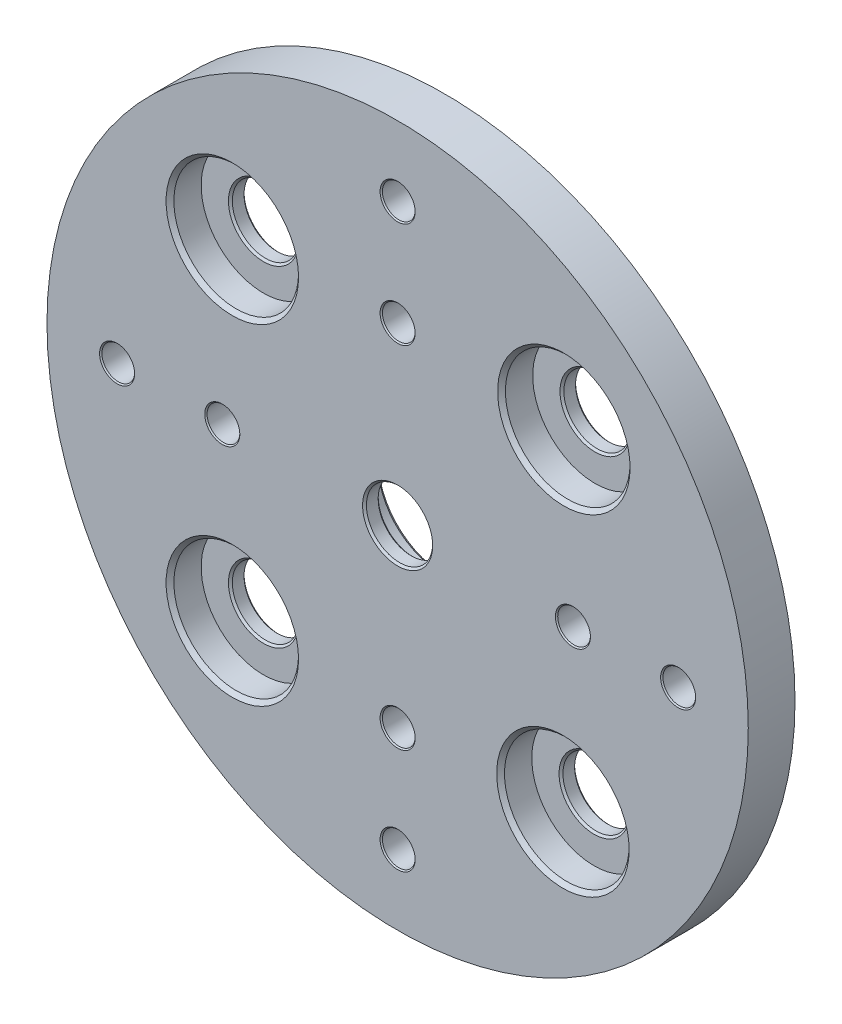
SolidWorks part; units mm, degrees
ref_plane "Front Plane" through (0, 0, 0) normal (0, 0, 1) x (1, 0, 0)
ref_plane "Top Plane" through (0, 0, 0) normal (0, 1, 0) x (1, 0, 0)
ref_plane "Right Plane" through (0, 0, 0) normal (1, 0, 0) x (0, 0, -1)
sketch "Sketch1" plane through (0, 0, 0) normal (0, 0, 1) x (1, 0, 0)
  circle A0 centre (0, 0) radius 90
  dimension "D1" = 180
extrude "Boss-Extrude1" add sketch "Sketch1" along normal blind 12
sketch "Sketch2" plane through (0, 0, 12) normal (0, 0, 1) x (1, 0, 0)
  line L0 (-90, 0) -> (90, 0) construction
  line L1 (0, -90) -> (0, 90) construction
  line L2 (-63.6396, -63.6396) -> (63.6396, 63.6396) construction
  line L3 (-63.6396, 63.6396) -> (63.6396, -63.6396) construction
  circle A0 centre (0, 0) radius 90 construction
  circle A1 centre (0, 0) radius 72 construction
  circle A2 centre (0, 0) radius 60 construction
  circle A3 centre (0, 0) radius 45 construction
  point P7 (0, 0)
  point P11 (0, 0)
  point P14 (0, 0)
  point P17 (0, 0)
  point P21 (0, 0)
  dimension "D3" = 144
  dimension "D4" = 120
  dimension "D5" = 90
  dimension "D1" = 45
  dimension "D2" = 45
hole_wizard "CBORE for M5 Hex Head Bolt1" positions "3DSketch1" profile "Sketch4" counterbore size "M5" standard "ANSI Metric" end condition through all
sketch3d "3DSketch1"
  line L0 (-63.6396, -63.6396, 12) -> (63.6396, 63.6396, 12) construction
  line L1 (-63.6396, 63.6396, 12) -> (63.6396, -63.6396, 12) construction
  circle A0 centre (0, 0, 12) radius 60 construction
  point P0 (42.6667, 42.6667, 12)
  point P4 (42.4264, -42.4264, 12)
  point P10 (0, 0, 72)
  point P11 (-42.4264, -42.4264, 12)
  point P13 (-42.4264, 42.4264, 12)
sketch "Sketch4" plane through (42.6667, 42.6667, 12) normal (1, 0, 0) x (0, -1, 0)
  line L0 (0, 0) -> (0, 12)
  line L1 (8.5, 11.5) -> (9, 12)
  line L2 (8.5, 11.5) -> (8.5, 8.5)
  line L3 (8.5, 8.5) -> (9, 8)
  line L4 (9, 8) -> (16, 8)
  line L5 (16, 8) -> (16, 1)
  line L6 (16, 1) -> (17, 0)
  line L7 (17, 0) -> (0, 0)
  line L8 (-16, 1) -> (-17, 0) construction
  line L9 (-8.5, 8.5) -> (-9, 8) construction
  line L11 (0, -6.35) -> (0, 107.95) construction
  line L12 (9, 12) -> (0, 12)
  line L13 (-8.5, 11.5) -> (-9, 12) construction
  dimension "Thru Hole Dia." = 17
  dimension "Thru Hole Depth" = 12
  dimension "C'Bore Dia." = 32
  dimension "C'Bore Depth" = 8
  dimension "Near C'Sink Dia." = 34
  dimension "Near C'Sink Angle" = 90
  dimension "Mid C'Sink Dia." = 18
  dimension "Mid C'Sink Angle" = 90
  dimension "Far C'Sink Dia." = 18
  dimension "Far C'Sink Angle" = 90
hole_wizard "CBORE for M5 Hex Head Bolt2" positions "3DSketch2" profile "Sketch5" counterbore size "M5" standard "ANSI Metric" end condition through all
sketch3d "3DSketch2"
  point P0 (0, 0, 0)
  point P4 (0, 0, 0)
sketch "Sketch5" plane through (0, 0, 0) normal (1, 0, 0) x (0, 1, 0)
  line L0 (0, 0) -> (0, 12)
  line L1 (8.5, 11.5) -> (9, 12)
  line L2 (8.5, 11.5) -> (8.5, 8.5)
  line L3 (8.5, 8.5) -> (9, 8)
  line L4 (9, 8) -> (16, 8)
  line L5 (16, 8) -> (16, 1)
  line L6 (16, 1) -> (17, 0)
  line L7 (17, 0) -> (0, 0)
  line L8 (-16, 1) -> (-17, 0) construction
  line L9 (-8.5, 8.5) -> (-9, 8) construction
  line L11 (0, -6.35) -> (0, 107.95) construction
  line L12 (9, 12) -> (0, 12)
  line L13 (-8.5, 11.5) -> (-9, 12) construction
  dimension "Thru Hole Dia." = 17
  dimension "Thru Hole Depth" = 12
  dimension "C'Bore Dia." = 32
  dimension "C'Bore Depth" = 8
  dimension "Near C'Sink Dia." = 34
  dimension "Near C'Sink Angle" = 90
  dimension "Mid C'Sink Dia." = 18
  dimension "Mid C'Sink Angle" = 90
  dimension "Far C'Sink Dia." = 18
  dimension "Far C'Sink Angle" = 90
hole_wizard "CSK for M5 Flat Head Machine Screw1" positions "3DSketch3" profile "Sketch6" countersink size "M5" standard "ANSI Metric" end condition through all
sketch3d "3DSketch3"
  point P0 (44.992, -0.0034, 0)
  point P2 (-0.0014, 44.9966, 0)
  point P4 (-45.0036, 0.0015, 0)
  point P6 (0.0018, -44.9961, 0)
sketch "Sketch6" plane through (44.992, -0.0034, 0) normal (1, 0, 0) x (0, 1, 0)
  line L0 (0, 0) -> (0, 12)
  line L1 (0, 12) -> (4.5, 12)
  line L2 (4.2, 11.7) -> (4.2, 4.8)
  line L3 (4.2, 4.8) -> (9, 0)
  line L5 (9, 0) -> (0, 0)
  line L6 (-4.2, 4.8) -> (-9, 0) construction
  line L7 (4.5, 12) -> (4.2, 11.7)
  line L8 (-4.5, 12) -> (-4.2, 11.7) construction
  line L11 (0, -6.35) -> (0, 107.95) construction
  dimension "Thru Hole Dia." = 8.4
  dimension "Thru Hole Depth" = 12
  dimension "Near C'Sink Dia." = 18
  dimension "Near C'Sink Angle" = 90
  dimension "Far C'Sink Dia." = 9
  dimension "Far C'Sink Angle" = 90
hole_wizard "CSK for M5 Flat Head Machine Screw2" positions "3DSketch5" profile "Sketch8" countersink size "M5" standard "ANSI Metric" end condition through all
sketch3d "3DSketch5"
  line L0 (-90, 0, 12) -> (90, 0, 12) construction
  line L1 (0, -90, 12) -> (0, 90, 12) construction
  circle A0 centre (0, 0, 12) radius 72 construction
  point P0 (-72, 0, 12)
  point P6 (0, 0, 84)
  point P7 (0, 72, 12)
  point P11 (72, 0, 12)
  point P13 (0, -72, 12)
sketch "Sketch8" plane through (-72, 0, 12) normal (1, 0, 0) x (0, -1, 0)
  line L0 (0, 0) -> (0, 12)
  line L1 (0, 12) -> (4.5, 12)
  line L2 (4.2, 11.7) -> (4.2, 0.3)
  line L3 (4.2, 0.3) -> (4.5, 0)
  line L5 (4.5, 0) -> (0, 0)
  line L6 (-4.2, 0.3) -> (-4.5, 0) construction
  line L7 (4.5, 12) -> (4.2, 11.7)
  line L8 (-4.5, 12) -> (-4.2, 11.7) construction
  line L11 (0, -6.35) -> (0, 107.95) construction
  dimension "Thru Hole Dia." = 8.4
  dimension "Thru Hole Depth" = 12
  dimension "Near C'Sink Dia." = 9
  dimension "Near C'Sink Angle" = 90
  dimension "Far C'Sink Dia." = 9
  dimension "Far C'Sink Angle" = 90
equation "\"a\"= 1"
equation "\"b\"= 1"
equation "\"c\"= 1"
equation "\"d\"= 1"
equation "\"e\"= 1"
equation "\"x\"= 1"
equation "\"y\"= 1"
equation "\"z\"= 1"
